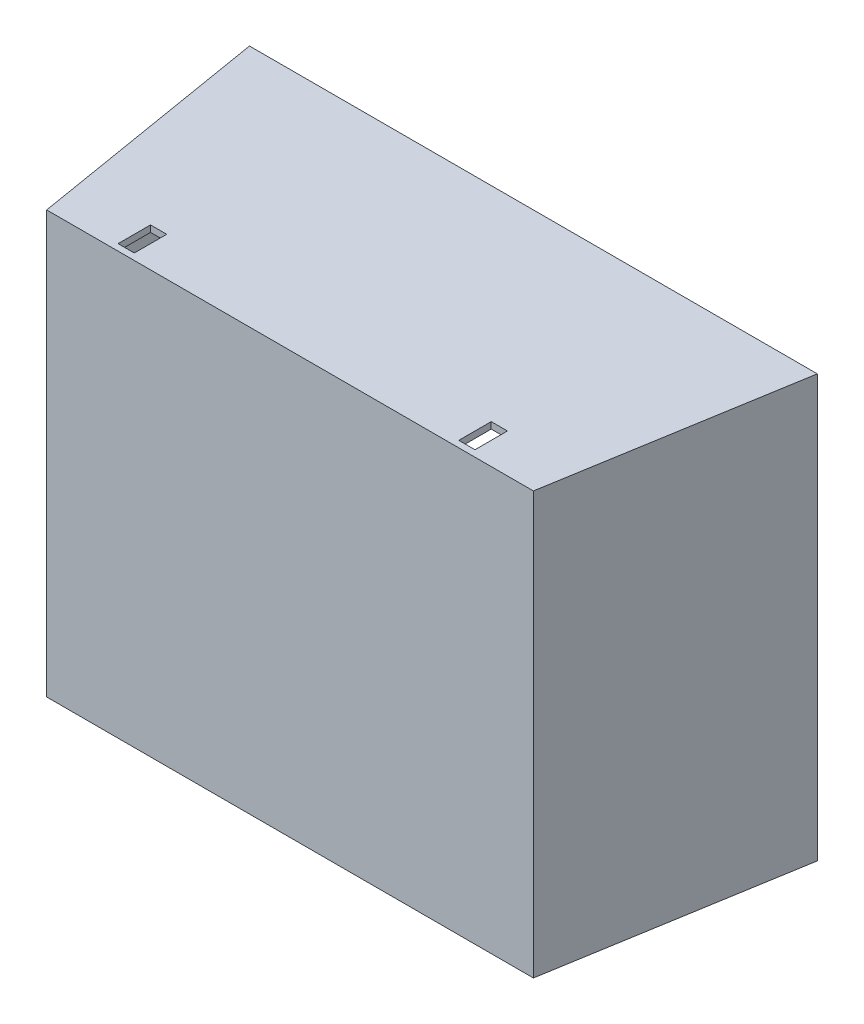
SolidWorks part; units mm, degrees
ref_plane "前视基准面" through (0, 0, 0) normal (0, 0, 1) x (1, 0, 0)
ref_plane "上视基准面" through (0, 0, 0) normal (0, 1, 0) x (1, 0, 0)
ref_plane "右视基准面" through (0, 0, 0) normal (1, 0, 0) x (0, 0, -1)
other "Configuration Table"
sketch "草图1" plane through (0, 0, 0) normal (0, 1, 0) x (1, 0, 0)
  line L5 (175, 0) -> (-175, 0)
  line L6 (0, 0) -> (0, -150)
  line L7 (-150, -150) -> (150, -150)
  line L8 (150, -150) -> (175, 0)
  line L9 (-150, -150) -> (-175, 0)
  point P0 (0, 0)
  dimension "D1" = 175
  dimension "D2" = 150
  dimension "D3" = 150
extrude "凸台-拉伸2" add sketch "草图1" along normal mid plane 260 contours L5 L9 L7 L8
shell "抽壳2" thickness 4
sketch "草图5" plane through (0, 130, 0) normal (0, 1, 0) x (1, 0, 0)
  line L0 (0, 0) -> (0, -150) construction
  line L1 (175, 0) -> (-175, 0) construction
  line L2 (-150, -150) -> (150, -150) construction
  line L3 (-100, -126) -> (-110, -126)
  line L4 (100, -146) -> (110, -146)
  line L5 (100, -146) -> (100, -126)
  line L6 (100, -126) -> (110, -126)
  line L7 (110, -146) -> (110, -126)
  line L8 (-110, -146) -> (-110, -126)
  line L9 (-100, -146) -> (-110, -146)
  line L10 (-100, -146) -> (-100, -126)
  dimension "D1" = 4
  dimension "D2" = 20
  dimension "D3" = 10
  dimension "D4" = 100
extrude "切除-拉伸1" cut sketch "草图5" against normal blind 260
